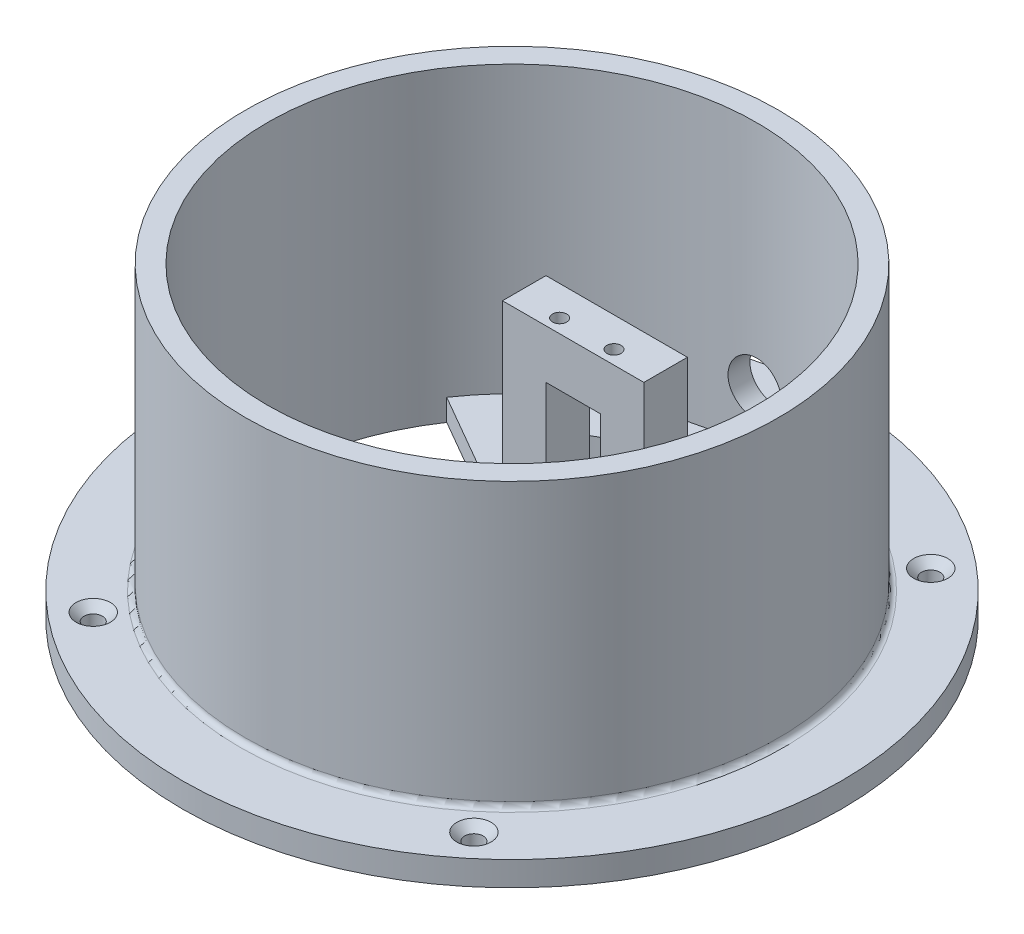
SolidWorks part; units mm, degrees
ref_plane "Front Plane" through (0, 0, 0) normal (0, 0, 1) x (1, 0, 0)
ref_plane "Top Plane" through (0, 0, 0) normal (0, 1, 0) x (1, 0, 0)
ref_plane "Right Plane" through (0, 0, 0) normal (1, 0, 0) x (0, 0, -1)
sketch "Sketch2" plane through (0, 0, 0) normal (0, 1, 0) x (1, 0, 0)
  circle A0 centre (0, 0) radius 60.625
  circle A1 centre (0, 0) radius 45
  dimension "D1" = 121.25
  dimension "D2" = 90
extrude "Boss-Extrude1" add sketch "Sketch2" along normal blind 4.5
sketch "Sketch3" plane through (0, 4.5, 0) normal (0, 1, 0) x (1, 0, 0)
  circle A2 centre (0, 0) radius 45 construction
  circle A4 centre (0, 0) radius 49
  circle A5 centre (0, 0) radius 49
  circle A6 centre (0, 0) radius 45
  dimension "D1" = 4
extrude "Boss-Extrude2" add sketch "Sketch3" along normal blind 52
sketch "Sketch4" plane through (0, 0, 0) normal (1, 0, 0) x (0, 0, -1)
  line L0 (-46.75, 38.5) -> (-31.75, 38.5)
  line L1 (-31.75, 38.5) -> (-31.75, 30.5)
  line L2 (-31.75, 30.5) -> (-46.75, 30.5)
  line L3 (-46.75, 30.5) -> (-46.75, 38.5)
  line L4 (-45, 56.5) -> (-45, 0)
  line L5 (-31.75, 30.5) -> (-45, 17.25)
  line L6 (-45, 0) -> (45, 0) construction
  line L7 (11.25, 38.5) -> (19.25, 38.5)
  line L8 (11.25, 38.5) -> (11.25, 0)
  line L9 (11.25, 0) -> (19.25, 0)
  line L10 (19.25, 38.5) -> (19.25, 0)
  line L11 (11.25, 38.5) -> (19.25, 0) construction
  line L12 (11.25, 0) -> (19.25, 38.5) construction
  line L13 (49, 56.5) -> (-49, 56.5) construction
  line L14 (45, 56.5) -> (-45, 56.5) construction
  point P8 (15.25, 19.25)
  dimension "D1" = 8
  dimension "D2" = 18
  dimension "D3" = 11.25
  dimension "D4" = 43
  dimension "D5" = 15
  dimension "D6" = 8
  dimension "D7" = 45
  dimension "D8" = 18
extrude "Boss-Extrude3" add sketch "Sketch4" along normal mid plane 26 contours L5 L2 L4 | L0 L4 L2 L1 | L10 L7 L8 L9
sketch "Sketch5" plane through (0, 0, 0) normal (0, 0, 1) x (1, 0, 0)
  line L6 (-5, 29.5) -> (5, 29.5)
  line L7 (-5, 29.5) -> (-5, 9.5)
  line L9 (5, 29.5) -> (5, 9.5)
  line L10 (-5, 29.5) -> (5, 9.5) construction
  line L11 (-5, 9.5) -> (5, 29.5) construction
  line L12 (13, 38.5) -> (-13, 38.5) construction
  line L14 (5, 9.5) -> (-5, 9.5)
  line L15 (49, 4.5) -> (-49, 4.5) construction
  point P0 (0, 19.5)
  point P5 (0, 9.5)
  dimension "D1" = 10
  dimension "D2" = 9
  dimension "D3" = 5
extrude "Cut-Extrude1" cut sketch "Sketch5" against normal blind 26
sketch "Sketch6" plane through (0, 0, -11.25) normal (0, 0, 1) x (1, 0, 0)
  line L0 (-60.625, 0) -> (60.625, 0) construction
  circle A0 centre (0, 14) radius 5
  dimension "D1" = 10
  dimension "D2" = 14
extrude "Cut-Extrude2" cut sketch "Sketch6" against normal through all
sketch "Sketch7" plane through (0, 38.5, 0) normal (0, 1, 0) x (1, 0, 0)
  line L0 (-5, -34.25) -> (5, -34.25) construction
  line L1 (-5, 13.75) -> (5, 13.75) construction
  line L2 (13, -31.75) -> (-13, -31.75) construction
  circle A0 centre (-5, 13.75) radius 1.3
  circle A1 centre (5, 13.75) radius 1.3
  circle A2 centre (-5, -34.25) radius 1.3
  circle A3 centre (5, -34.25) radius 1.3
  dimension "D1" = 2.6
  dimension "D2" = 5
  dimension "D3" = 10
  dimension "D4" = 10
  dimension "D5" = 2.5
  dimension "D6" = 48
extrude "Cut-Extrude3" cut sketch "Sketch7" against normal blind 7.2
sketch "Sketch8" plane through (0, 0, 0) normal (0, -1, 0) x (1, 0, 0)
  line L0 (13, -11.25) -> (-13, -11.25) construction
  line L1 (13, -11.25) -> (-13, -11.25)
  line L2 (-13, -11.25) -> (-37.2484, -25.2498)
  line L3 (0, 0) -> (0, -45) construction
  line L4 (13, -11.25) -> (37.2484, -25.2498)
  line L5 (-19.5167, -24.25) -> (-24.9065, -27.3618)
  line L6 (19.5167, -24.25) -> (24.9065, -27.3618)
  line L8 (-19.5167, -24.25) -> (19.5167, -24.25)
  line L9 (-10.8564, -19.25) -> (-24.9065, -27.3618) construction
  line L10 (10.8564, -19.25) -> (-10.8564, -19.25) construction
  line L11 (10.8564, -19.25) -> (24.9065, -27.3618) construction
  line L12 (13, -19.25) -> (-13, -19.25) construction
  circle A0 centre (0, 0) radius 45 construction
  arc A1 (-37.2484, -25.2498) -> (37.2484, -25.2498) centre (0, 0) ccw
  arc A2 (-24.9065, -27.3618) -> (24.9065, -27.3618) centre (0, 0) ccw
  point P14 (22.0126, -24.25)
  dimension "D1" = 60
  dimension "D3" = 5
  dimension "D2" = 8
extrude "Boss-Extrude4" add sketch "Sketch8" against normal blind 4
sketch "Sketch9" plane through (0, 4.5, 0) normal (0, 1, 0) x (1, 0, 0)
  line L1 (-35, 42) -> (35, 42) construction
  line L2 (-35, 42) -> (-35, -42) construction
  line L3 (-35, -42) -> (35, -42) construction
  line L4 (35, 42) -> (35, -42) construction
  line L5 (-35, 42) -> (35, -42) construction
  line L6 (-35, -42) -> (35, 42) construction
  point P0 (0, 0)
  dimension "D1" = 84
  dimension "D2" = 70
hole_wizard "CSK for M3 Countersunk Flat Head Screw1" positions "3DSketch1" profile "Sketch10" countersink size "M3" standard "DIN"
sketch3d "3DSketch1"
  point P0 (-35, 4.5, -42)
  point P3 (35, 4.5, -42)
  point P6 (35, 4.5, 42)
  point P9 (-35, 4.5, 42)
sketch "Sketch10" plane through (-35, 4.5, -42) normal (1, 0, 0) x (0, 0, 1)
  line L0 (0, 0) -> (0, 45.4715)
  line L1 (0, 45.4715) -> (1.7, 44.45)
  line L2 (1.7, 44.45) -> (1.7, 1.45)
  line L3 (1.7, 1.45) -> (3.15, 0)
  line L5 (3.15, 0) -> (0, 0)
  line L6 (-1.7, 1.45) -> (-3.15, 0) construction
  line L10 (0, 45.4715) -> (-1.7, 44.45) construction
  line L11 (0, -6.35) -> (0, 107.95) construction
  dimension "Hole Dia." = 3.4
  dimension "Hole Depth" = 44.45
  dimension "Near C'Sink Dia." = 6.3
  dimension "Near C'Sink Angle" = 90
  dimension "Drill Angle" = 118
fillet "Fillet1" radius 1 1 edges at (0, 4.5, 49)
